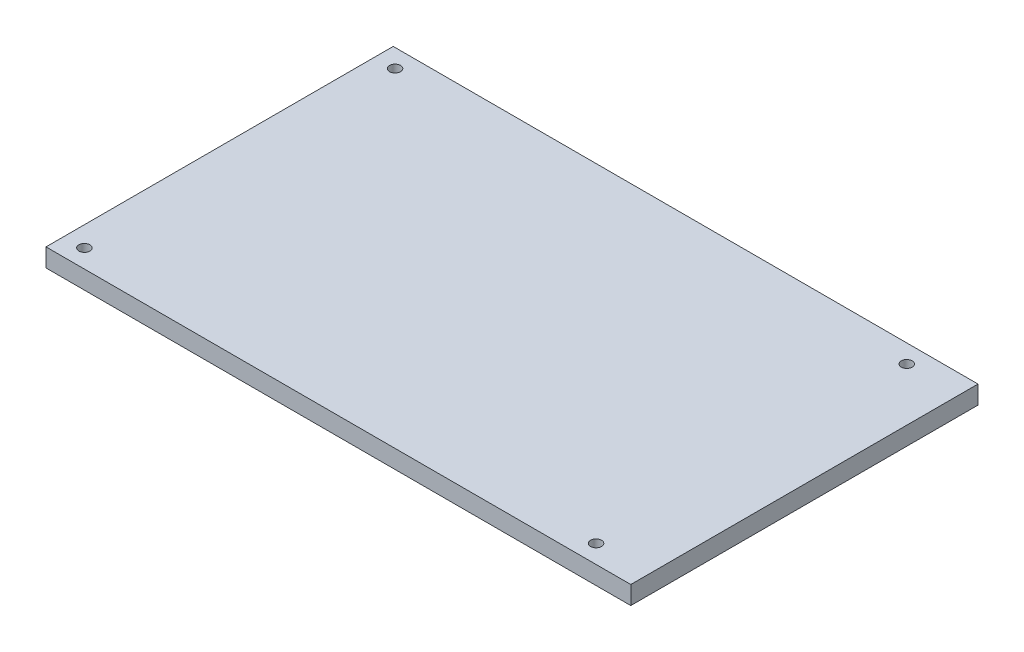
SolidWorks part; units mm, degrees
ref_plane "前视基准面" through (0, 0, 0) normal (0, 0, 1) x (1, 0, 0)
ref_plane "上视基准面" through (0, 0, 0) normal (0, 1, 0) x (1, 0, 0)
ref_plane "右视基准面" through (0, 0, 0) normal (1, 0, 0) x (0, 0, -1)
other "Configuration Table"
sketch "草图1" plane through (0, 0, 0) normal (0, 1, 0) x (1, 0, 0)
  line L1 (0, 0) -> (160, 0)
  line L2 (0, 0) -> (0, 95)
  line L3 (0, 95) -> (160, 95)
  line L4 (160, 0) -> (160, 95)
  dimension "D1" = 160
  dimension "D2" = 95
extrude "凸台-拉伸1" add sketch "草图1" along normal blind 5
sketch "草图2" plane through (0, 5, 0) normal (0, 1, 0) x (1, 0, 0)
  line L0 (0, 47.5) -> (166.3822, 47.5) construction
  line L1 (0, 95) -> (0, 0) construction
  circle A0 centre (5.5, 90) radius 1.5
  circle A1 centre (145.5, 90) radius 1.5
  circle A2 centre (145.5, 5) radius 1.5
  circle A3 centre (5.5, 5) radius 1.5
  dimension "D1" = 3
  dimension "D2" = 85
  dimension "D3" = 140
  dimension "D4" = 5.5
extrude "切除-拉伸1" cut sketch "草图2" against normal through all
